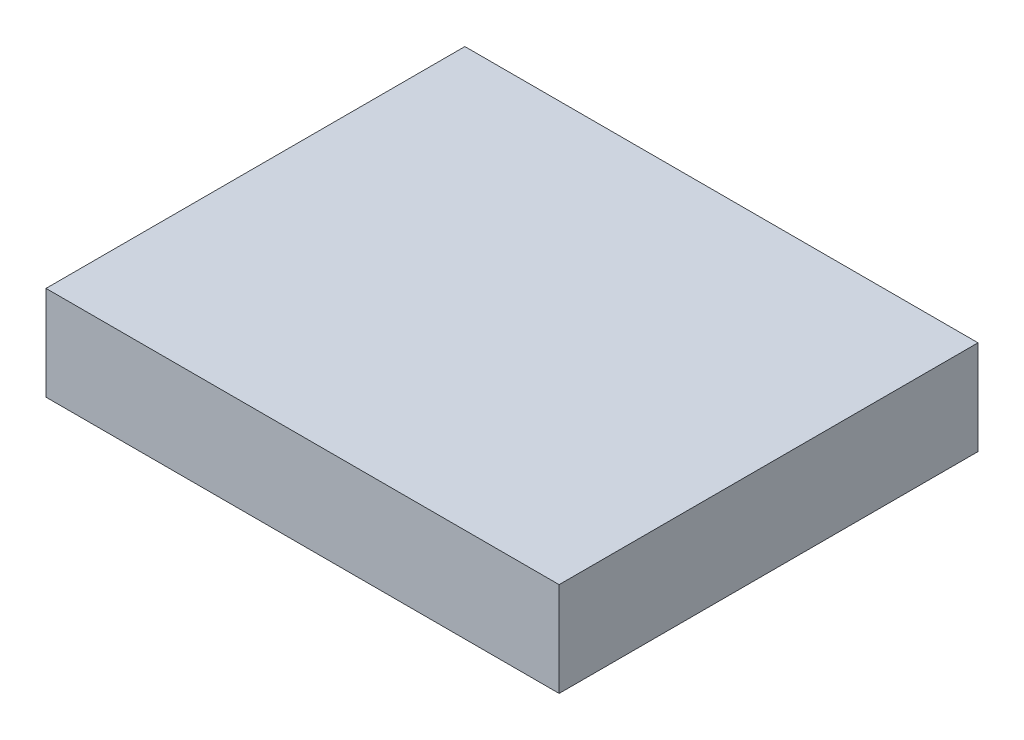
SolidWorks part; units mm, degrees
ref_plane "Front Plane" through (0, 0, 0) normal (0, 0, 1) x (1, 0, 0)
ref_plane "Top Plane" through (0, 0, 0) normal (0, 1, 0) x (1, 0, 0)
ref_plane "Right Plane" through (0, 0, 0) normal (1, 0, 0) x (0, 0, -1)
sketch "Sketch1" plane through (0, 0, 0) normal (0, 0, 1) x (1, 0, 0)
  line L0 (-36.75, 6.75) -> (36.75, 6.75)
  line L1 (-37.5, 7.5) -> (37.5, 7.5) construction
  line L2 (-37.5, 7.5) -> (-37.5, -7.5) construction
  line L3 (-37.5, -7.5) -> (37.5, -7.5) construction
  line L4 (37.5, 7.5) -> (37.5, -7.5) construction
  line L5 (-37.5, 7.5) -> (37.5, -7.5) construction
  line L6 (-37.5, -7.5) -> (37.5, 7.5) construction
  line L7 (36.75, 6.75) -> (36.75, -6.75)
  line L8 (-36.75, -6.75) -> (36.75, -6.75)
  line L9 (-36.75, 6.75) -> (-36.75, -6.75)
  point P0 (0, 0)
  dimension "D1" = 15
  dimension "D2" = 75
  dimension "D3" = 0.75
extrude "Boss-Extrude1" add sketch "Sketch1" along normal mid plane 60 from offset 0
